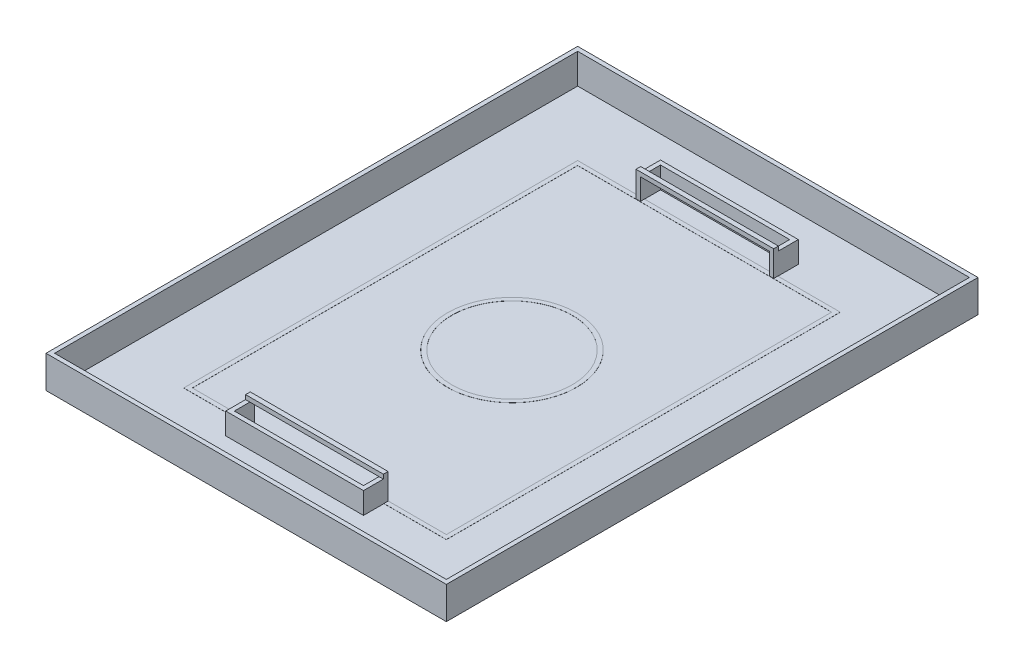
SolidWorks part; units mm, degrees
ref_plane "Plano frontal" through (0, 0, 0) normal (0, 0, 1) x (1, 0, 0)
ref_plane "Plano superior" through (0, 0, 0) normal (0, 1, 0) x (1, 0, 0)
ref_plane "Plano direito" through (0, 0, 0) normal (1, 0, 0) x (0, 0, -1)
sketch "Esboço1" plane through (0, 0, 0) normal (0, 1, 0) x (1, 0, 0)
  line L1 (0, 0) -> (1860, 0)
  line L2 (0, 0) -> (0, 2470)
  line L3 (0, 2470) -> (1860, 2470)
  line L4 (1860, 0) -> (1860, 2470)
  dimension "D1" = 1860
  dimension "D2" = 2470
extrude "Ressalto-extrusão1" add sketch "Esboço1" along normal blind 10
sketch "Esboço2" plane through (0, 10, 0) normal (0, 1, 0) x (1, 0, 0)
  line L0 (1840, 20) -> (20, 20)
  line L1 (1860, 0) -> (0, 0)
  line L2 (1860, 0) -> (1860, 2470)
  line L3 (1860, 2470) -> (0, 2470)
  line L4 (0, 0) -> (0, 2470)
  line L5 (20, 20) -> (20, 2450)
  line L6 (1840, 2450) -> (20, 2450)
  line L7 (1840, 20) -> (1840, 2450)
  dimension "D1" = 20
extrude "Ressalto-extrusão2" add sketch "Esboço2" along normal blind 140
sketch "Esboço3" plane through (0, 10, 0) normal (0, 1, 0) x (1, 0, 0)
  line L0 (20, 1235) -> (1840, 1235) construction
  line L1 (20, 2450) -> (20, 20) construction
  line L2 (1840, 20) -> (1840, 2450) construction
  line L3 (340, 2130) -> (1520, 2130)
  line L4 (320, 2150) -> (1540, 2150)
  line L5 (320, 2150) -> (320, 320)
  line L6 (320, 320) -> (1540, 320)
  line L7 (1540, 2150) -> (1540, 320)
  line L8 (320, 2150) -> (1540, 320) construction
  line L9 (320, 320) -> (1540, 2150) construction
  line L10 (1520, 2130) -> (1520, 340)
  line L11 (340, 340) -> (1520, 340)
  line L12 (340, 2130) -> (340, 340)
  circle A0 centre (930, 1235) radius 300
  circle A1 centre (930, 1235) radius 280
  point P6 (930, 1235)
  dimension "D4" = 600
  dimension "D1" = 1220
  dimension "D2" = 1830
  dimension "D3" = 20
  dimension "D5" = 20
extrude "Ressalto-extrusão3" add sketch "Esboço3" along normal blind 0.5 contours A0 A1 | L7 L4 L5 L6 L12 L3 L10 L11
sketch "Esboço4" plane through (0, 10, 0) normal (0, 1, 0) x (1, 0, 0)
  line L0 (930, 2450) -> (930, 2068.4702) construction
  line L1 (1840, 2450) -> (20, 2450) construction
  line L3 (630, 2224.9413) -> (1230, 2224.9413)
  line L4 (630, 2224.9413) -> (630, 2150.9413)
  line L6 (1230, 2224.9413) -> (1230, 2150.9413)
  line L7 (630, 2224.9413) -> (1230, 2150.9413) construction
  line L8 (630, 2150.9413) -> (1230, 2224.9413) construction
  line L10 (610, 2244.9413) -> (1250, 2244.9413)
  line L11 (1250, 2244.9413) -> (1250, 2130.9413)
  line L12 (610, 2130.9413) -> (630, 2130.9413)
  line L13 (610, 2244.9413) -> (610, 2130.9413)
  line L14 (1230, 2150.9413) -> (1230, 2130.9413)
  line L15 (630, 2150.9413) -> (630, 2130.9413)
  line L16 (1230, 2130.9413) -> (1250, 2130.9413)
  line L17 (610, 2130.9413) -> (1250, 2130.9413) construction
  line L18 (630, 2150.9413) -> (1230, 2150.9413) construction
  point P4 (930, 2187.9413)
  dimension "D1" = 74
  dimension "D2" = 600
  dimension "D3" = 20
extrude "Ressalto-extrusão4" add sketch "Esboço4" along normal blind 100
sketch "Esboço5" plane through (0, 110, 0) normal (0, 1, 0) x (1, 0, 0)
  line L0 (1250, 2130.9413) -> (1250, 2244.9413) construction
  line L1 (610, 2130.9413) -> (1250, 2130.9413)
  line L2 (610, 2130.9413) -> (610, 2152.7832)
  line L3 (610, 2152.7832) -> (1250, 2152.7832)
  line L4 (1250, 2130.9413) -> (1250, 2152.7832)
extrude "Ressalto-extrusão5" add sketch "Esboço5" along normal blind 20
pattern_circular "PadrãoCircular1" count 2 over 360 about axis through (930, 10.5, -1235) along (0, 1, 0) of "Ressalto-extrusão4", "Ressalto-extrusão5"
